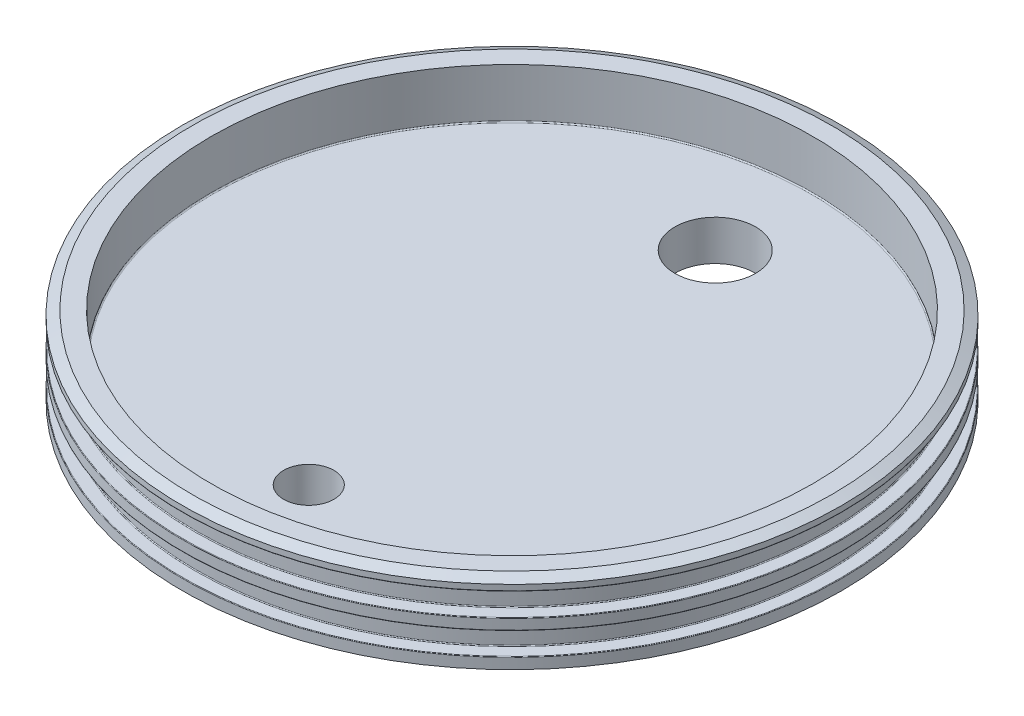
SolidWorks part; units mm, degrees
material "6061-T6 (SS)"
ref_plane "Front Plane" through (0, 0, 0) normal (0, 0, 1) x (1, 0, 0)
ref_plane "Top Plane" through (0, 0, 0) normal (0, 1, 0) x (1, 0, 0)
ref_plane "Right Plane" through (0, 0, 0) normal (1, 0, 0) x (0, 0, -1)
sketch "Sketch1" plane through (0, 0, 0) normal (0, 0, 1) x (1, 0, 0)
  line L0 (0, 48.1922) -> (0, -25.6743) construction
  line L1 (0, 0) -> (72.898, 0)
  line L2 (72.898, 0) -> (72.898, 2.4638)
  line L3 (72.898, 2.4638) -> (69.977, 2.4638)
  line L4 (69.977, 2.4638) -> (69.977, 7.4422)
  line L5 (69.977, 7.4422) -> (72.898, 7.4422)
  line L6 (72.898, 7.4422) -> (72.898, 9.906)
  line L7 (72.898, 9.906) -> (69.977, 9.906)
  line L8 (66.548, 17.3482) -> (66.548, 6.35)
  line L9 (66.548, 6.35) -> (0, 6.35)
  line L10 (0, 6.35) -> (0, 0)
  line L11 (69.977, 9.906) -> (69.977, 14.986)
  line L12 (69.977, 14.986) -> (72.898, 14.986)
  line L13 (72.898, 14.986) -> (72.898, 17.3482)
  line L14 (72.898, 17.3482) -> (66.548, 17.3482)
  dimension "D1" = 145.796
  dimension "D2" = 4.9784
  dimension "D3" = 2.921
  dimension "D4" = 9.906
  dimension "D5" = 6.35
  dimension "D6" = 6.35
  dimension "D7" = 5.08
  dimension "D8" = 9.906
revolve "Revolve1" add sketch "Sketch1" angle 360 about L0
sketch "Sketch6" plane through (0, 0, 0) normal (0, -1, 0) x (1, 0, 0)
  circle A0 centre (0, 0) radius 66.04
  dimension "D1" = 132.08
extrude "Boss-Extrude1" add sketch "Sketch6" along normal blind 2.54
fillet "CNC ID Fillet" radius 0.1778 5 edges at (-69.977, 7.4422, 0) (-69.977, 2.4638, 0) (66.04, 0, 0) (-69.977, 14.986, 0) (-69.977, 9.906, 0)
fillet "CNC OD Fillet" radius 0.127 5 edges at (-72.898, 7.4422, 0) (-72.898, 2.4638, 0) (-72.898, 9.906, 0) (-72.898, 14.986, 0) (66.04, -2.54, 0)
chamfer "CNC Chamfers" distance 1.016 angle 65 1 edges at (-72.898, 17.3482, 0)
fillet "CNC Bore Fillet" radius 0.254 1 edges at (-66.548, 6.35, 0)
hole_wizard "Pipe Tap Drill for 1/2 Tap - Fill Valve" positions "Sketch13" profile "Sketch14" hole size "1/2" standard "ANSI Inch" end condition through all
sketch "Sketch13" plane through (0, -2.54, 0) normal (0, -1, 0) x (-1, 0, 0)
  point P4 (0, 44.958)
  dimension "D1" = 44.958
sketch "Sketch14" plane through (0, -2.54, -44.958) normal (1, 0, 0) x (0, 0, -1)
  line L0 (0, 0) -> (0, 19.8882)
  line L1 (0, 19.8882) -> (8.9281, 19.8882)
  line L2 (8.9281, 19.8882) -> (8.9281, 0)
  line L5 (8.9281, 0) -> (0, 0)
  line L11 (0, -6.35) -> (0, 107.95) construction
  dimension "Thru Hole Dia." = 17.8562
  dimension "Thru Hole Depth" = 19.8882
hole_wizard "Pipe Tap Drill for 1/4 Tap - Solenoid Valve" positions "Sketch15" profile "Sketch16" hole size "1/4" standard "ANSI Inch" end condition through all
sketch "Sketch15" plane through (0, -2.54, 0) normal (0, -1, 0) x (-1, 0, 0)
  point P4 (0, -44.958)
  dimension "D1" = 44.958
sketch "Sketch16" plane through (0, -2.54, 44.958) normal (1, 0, 0) x (0, 0, -1)
  line L0 (0, 0) -> (0, 19.8882)
  line L1 (0, 19.8882) -> (5.5626, 19.8882)
  line L2 (5.5626, 19.8882) -> (5.5626, 0)
  line L5 (5.5626, 0) -> (0, 0)
  line L11 (0, -6.35) -> (0, 107.95) construction
  dimension "Thru Hole Dia." = 11.1252
  dimension "Thru Hole Depth" = 19.8882
